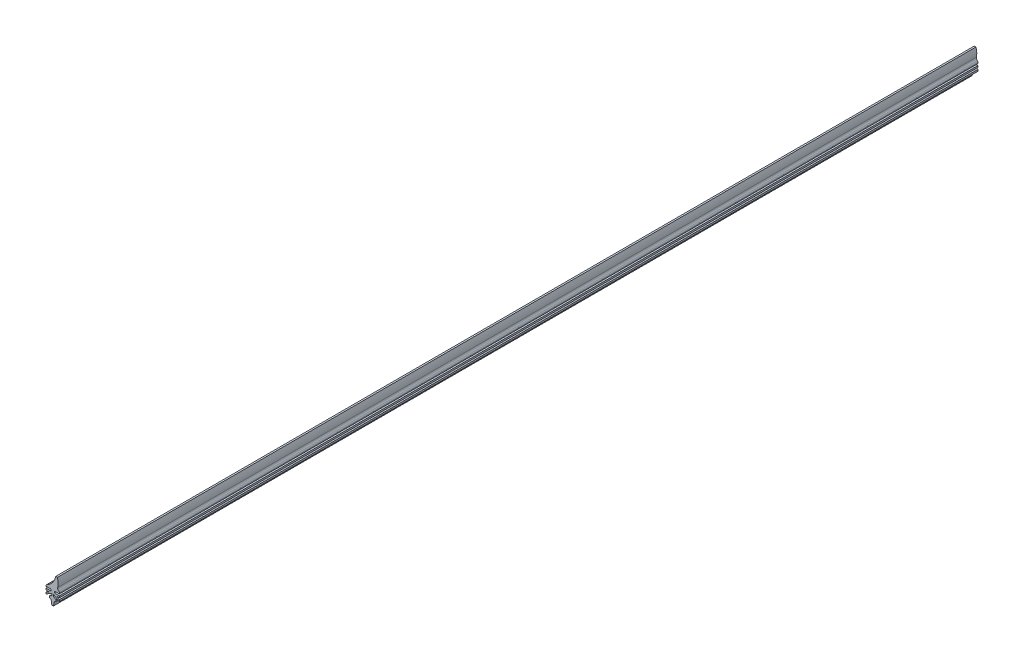
SolidWorks part; units mm, degrees
material "Caoutchouc"
ref_plane "Plan de face" through (0, 0, 0) normal (0, 0, 1) x (1, 0, 0)
ref_plane "Plan de dessus" through (0, 0, 0) normal (0, 1, 0) x (1, 0, 0)
ref_plane "Plan de droite" through (0, 0, 0) normal (1, 0, 0) x (0, 0, -1)
sketch "Esquisse1" plane through (0, 0, 0) normal (0, 0, 1) x (1, 0, 0)
  line L0 (0, 0) -> (0, -7.2441) construction
  line L1 (4, 0) -> (1, 0)
  line L2 (-8, 0) -> (-1, 0) construction
  line L3 (-4, 0) -> (-4, -1)
  line L4 (4, 0) -> (4, -1)
  line L5 (-4, -1) -> (-2.2647, -1)
  line L6 (4, -1) -> (2.2647, -1)
  line L7 (-2.2647, -1) -> (-4, -2)
  line L8 (2.2647, -1) -> (4, -2)
  line L9 (-4, -2) -> (-4, -3)
  line L10 (4, -2) -> (4, -3)
  line L11 (-4, -3) -> (-0.5, -0.9831)
  line L12 (4, -3) -> (0.5, -0.9831)
  line L13 (-0.5, -0.9831) -> (-0.5, -2.1372)
  line L14 (0.5, -0.9831) -> (0.5, -2.1372)
  line L15 (-0.5, -2.1372) -> (-2, -3.0016)
  line L16 (0.5, -2.1372) -> (2, -3.0016)
  line L17 (-2, -3.0016) -> (-2, -4.0016)
  line L18 (2, -3.0016) -> (2, -4.0016)
  line L19 (-2, -4.0016) -> (-1.8471, -4.0016)
  line L20 (2, -4.0016) -> (1.8471, -4.0016)
  line L21 (-0.8607, -4.8371) -> (-0.5, -7)
  line L22 (0.8607, -4.8371) -> (0.5, -7)
  line L23 (-0.5, -7) -> (0.5, -7)
  line L24 (1, 1) -> (8, 1) construction
  line L25 (0, 0) -> (0, 8.6585) construction
  line L26 (8, 1) -> (8, 0) construction
  line L27 (-8, 1) -> (-1, 1) construction
  line L28 (1.798, 9) -> (2.798, 9)
  line L29 (4, 1.5) -> (4, 1)
  line L30 (-4, 1.202) -> (-4, 1)
  line L31 (-8, 1) -> (-8, 0) construction
  line L32 (-1, 1) -> (-4, 1)
  line L33 (-1, 1) -> (-1, 0)
  line L34 (1, 0) -> (1, 1)
  line L35 (1, 1) -> (4, 1)
  line L36 (-1, 0) -> (-4, 0)
  arc A0 (0.8607, -4.8371) -> (1.8471, -4.0016) centre (1.8471, -5.0016) cw
  arc A1 (-0.8607, -4.8371) -> (-1.8471, -4.0016) centre (-1.8471, -5.0016) ccw
  arc A2 (-3.4545, 2.0928) -> (1.798, 9) centre (-8, 11) ccw
  arc A3 (3.035, 3.8221) -> (3.6, 2.3) centre (4.5, 3.5) ccw
  arc A4 (-4, 1.202) -> (-3.4545, 2.0928) centre (-3, 1.202) cw
  arc A5 (3.035, 3.8221) -> (2.798, 9) centre (-6.7317, 5.9694) ccw
  arc A6 (4, 1.5) -> (3.6, 2.3) centre (3, 1.5) ccw
  point P28 (0, -7)
  point P32 (1, -4.0016)
  point P35 (-1, -4.0016)
  dimension "D13" = 1
  dimension "D16" = 20
  dimension "D19" = 3
  dimension "D22" = 1
  dimension "D1" = 1
  dimension "D2" = 4
  dimension "D3" = 1
  dimension "D4" = 8
  dimension "D5" = 8
  dimension "D6" = 1
  dimension "D7" = 1
  dimension "D8" = 1
  dimension "D9" = 1
  dimension "D10" = 1
  dimension "D11" = 8
  dimension "D12" = 2
  dimension "D14" = 16
  dimension "D15" = 10
  dimension "D17" = 8
  dimension "D18" = 1
  dimension "D20" = 2.5
  dimension "D21" = 4.5
  dimension "D23" = 4
extrude "Extrusion1" add sketch "Esquisse1" against normal blind 550
